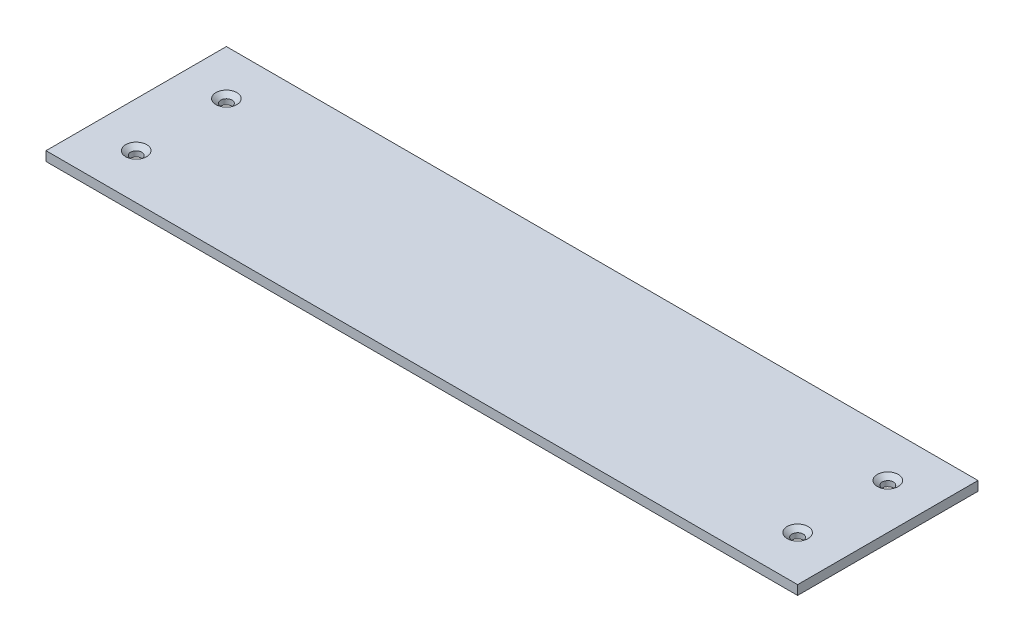
SolidWorks part; units mm, degrees
ref_plane "Front Plane" through (0, 0, 0) normal (0, 0, 1) x (1, 0, 0)
ref_plane "Top Plane" through (0, 0, 0) normal (0, 1, 0) x (1, 0, 0)
ref_plane "Right Plane" through (0, 0, 0) normal (1, 0, 0) x (0, 0, -1)
sketch "Sketch2" plane through (0, 0, 0) normal (0, 1, 0) x (1, 0, 0)
  line L1 (0, 0) -> (254, 0)
  line L2 (0, 0) -> (0, 60.96)
  line L3 (0, 60.96) -> (254, 60.96)
  line L4 (254, 0) -> (254, 60.96)
  dimension "D1" = 254
  dimension "D2" = 60.96
extrude "Boss-Extrude1" add sketch "Sketch2" along normal blind 3.175
hole_wizard "CSK for #6 Flat Head Machine Screw (100)1" positions "Sketch3" profile "Sketch5" countersink size "#6" standard "ANSI Inch"
sketch "Sketch3" plane through (0, 3.175, 0) normal (0, 1, 0) x (1, 0, 0)
  line L0 (0, 0) -> (254, 0) construction
  line L1 (0, 60.96) -> (0, 0) construction
  line L2 (254, 60.96) -> (0, 60.96) construction
  line L3 (254, 0) -> (254, 60.96) construction
  point P0 (15.24, 15.24)
  point P2 (15.24, 45.72)
  point P4 (238.76, 15.24)
  point P6 (238.76, 45.72)
  point P13 (0, 0)
  point P16 (0, 0)
  point P19 (0, 0)
  point P24 (244.6401, 63.7976)
  dimension "D1" = 15.24
  dimension "D2" = 15.24
  dimension "D3" = 15.24
  dimension "D4" = 15.24
  dimension "D5" = 15.24
  dimension "D6" = 15.24
  dimension "D7" = 15.24
  dimension "D8" = 15.24
sketch "Sketch5" plane through (15.24, 3.175, -15.24) normal (1, 0, 0) x (0, 0, 1)
  line L0 (0, 0) -> (0, 4.3158)
  line L1 (0, 4.3158) -> (1.8986, 3.175)
  line L2 (1.8986, 3.175) -> (1.8986, 1.38)
  line L3 (1.8986, 1.38) -> (3.5433, 0)
  line L5 (3.5433, 0) -> (0, 0)
  line L6 (-1.8986, 1.38) -> (-3.5433, 0) construction
  line L10 (0, 4.3158) -> (-1.8987, 3.175) construction
  line L11 (0, -6.35) -> (0, 107.95) construction
  dimension "Hole Dia." = 3.7973
  dimension "Hole Depth" = 3.175
  dimension "Near C'Sink Dia." = 7.0866
  dimension "Near C'Sink Angle" = 100
  dimension "Drill Angle" = 118
